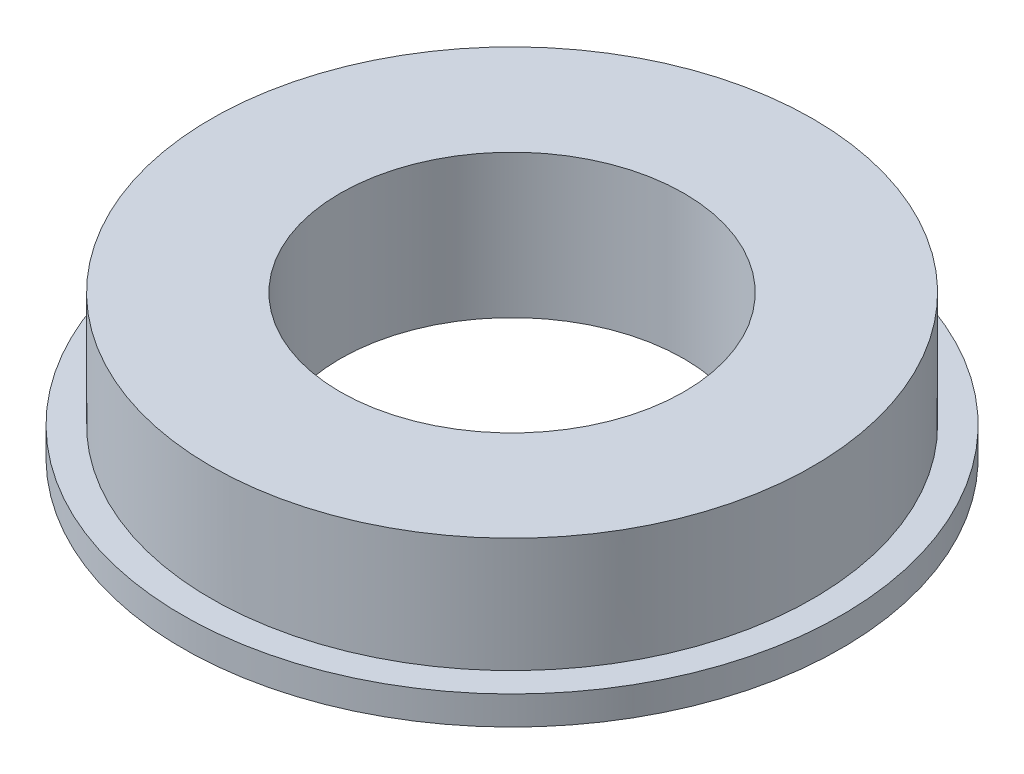
SolidWorks part; units mm, degrees
material "合金钢"
ref_plane "前视基准面" through (0, 0, 0) normal (0, 0, 1) x (1, 0, 0)
ref_plane "上视基准面" through (0, 0, 0) normal (0, 1, 0) x (1, 0, 0)
ref_plane "右视基准面" through (0, 0, 0) normal (1, 0, 0) x (0, 0, -1)
sketch "草图1" plane through (0, 0, 0) normal (0, 1, 0) x (1, 0, 0)
  circle A0 centre (0, 0) radius 10.5
  circle A1 centre (0, 0) radius 6
  dimension "D1" = 21
  dimension "D2" = 12
extrude "凸台-拉伸1" add sketch "草图1" along normal blind 5
sketch "草图2" plane through (0, 0, 0) normal (0, -1, 0) x (1, 0, 0)
  circle A0 centre (0, 0) radius 11.5
  circle M1 centre (0, 0) radius 10.5
  dimension "D1" = 23
extrude "凸台-拉伸2" add sketch "草图2" against normal blind 1 contours A0 M1
